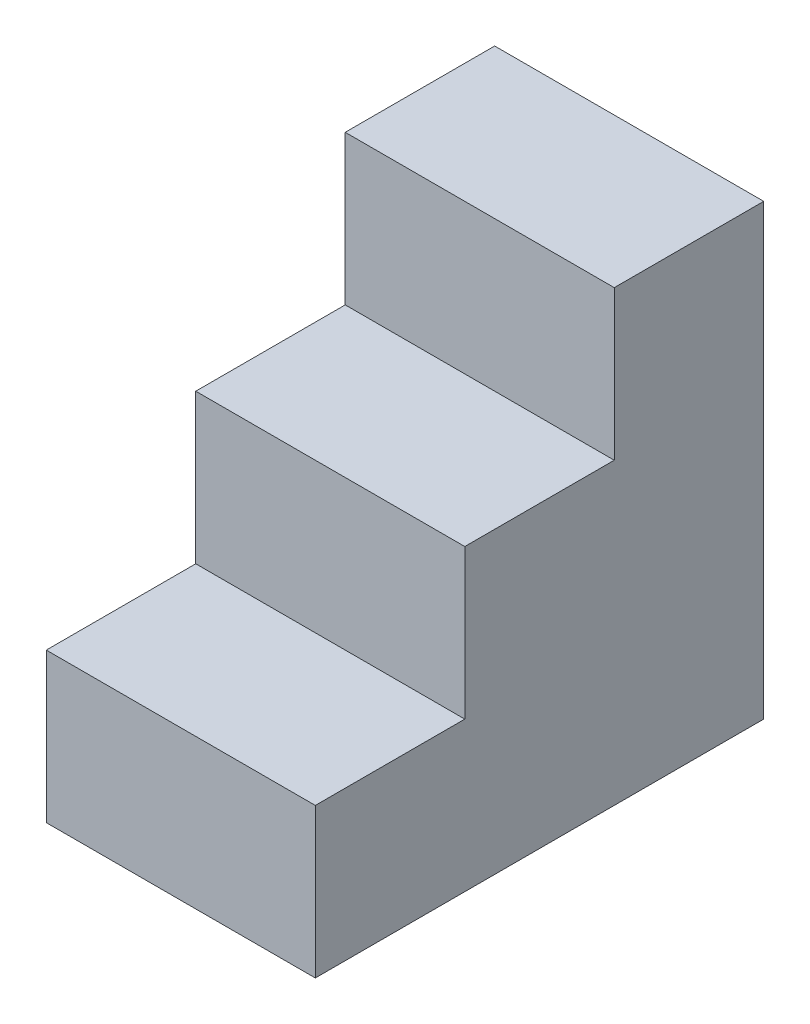
SolidWorks part; units mm, degrees
ref_plane "前视基准面" through (0, 0, 0) normal (0, 0, 1) x (1, 0, 0)
ref_plane "上视基准面" through (0, 0, 0) normal (0, 1, 0) x (1, 0, 0)
ref_plane "右视基准面" through (0, 0, 0) normal (1, 0, 0) x (0, 0, -1)
other "Configuration Table"
sketch "草图1" plane through (0, 0, 0) normal (1, 0, 0) x (0, 0, -1)
  line L0 (0, 0) -> (-11, 0)
  line L1 (-11, 0) -> (-11, -11)
  line L2 (-11, -11) -> (-22, -11)
  line L3 (-22, -11) -> (-22, -22)
  line L4 (-22, -22) -> (-33, -22)
  line L5 (-33, -22) -> (-33, -33)
  line L6 (-33, -33) -> (0, -33)
  line L7 (0, -33) -> (0, 0)
  dimension "D1" = 33
extrude "凸台-拉伸1" add sketch "草图1" along normal blind 19.8
